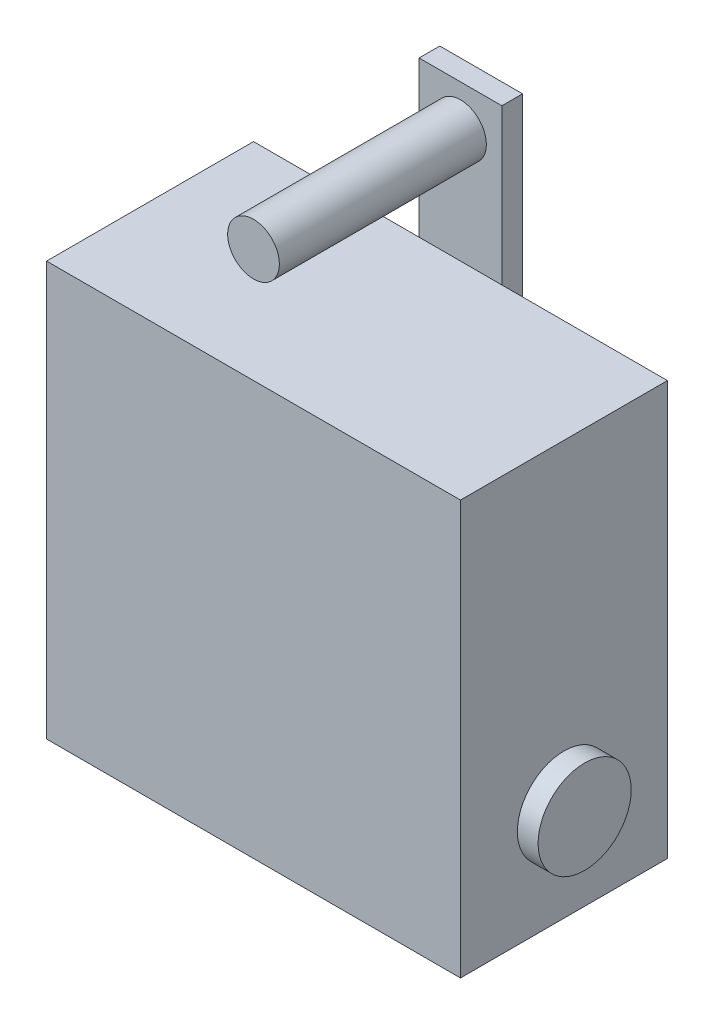
SolidWorks part; units mm, degrees
ref_plane "Plan de face" through (0, 0, 0) normal (0, 0, 1) x (1, 0, 0)
ref_plane "Plan de dessus" through (0, 0, 0) normal (0, 1, 0) x (1, 0, 0)
ref_plane "Plan de droite" through (0, 0, 0) normal (1, 0, 0) x (0, 0, -1)
sketch "Esquisse1" plane through (0, 0, 0) normal (0, 1, 0) x (1, 0, 0)
  line L1 (0, 0) -> (40, 0)
  line L2 (0, 0) -> (0, 20)
  line L3 (0, 20) -> (40, 20)
  line L4 (40, 0) -> (40, 20)
  dimension "D1" = 40
  dimension "D2" = 20
extrude "Boss.-Extru.1" add sketch "Esquisse1" along normal blind 40
sketch "Esquisse2" plane through (40, 0, 0) normal (1, 0, 0) x (0, 0, -1)
  line L2 (0, 0) -> (20, 0) construction
  line L3 (0, 40) -> (0, 0) construction
  circle A0 centre (10, 9.5) radius 4.5
  dimension "D1" = 9.5
  dimension "D2" = 9
  dimension "D3" = 10
extrude "Boss.-Extru.2" add sketch "Esquisse2" along normal blind 2
sketch "Esquisse3" plane through (0, 0, -20) normal (0, 0, -1) x (-1, 0, 0)
  line L0 (-24, 30) -> (-16, 30)
  line L1 (-24, 30) -> (-24, 55)
  line L2 (-16, 30) -> (-16, 55)
  line L3 (-24, 55) -> (-16, 55)
  line L4 (-40, 40) -> (0, 40) construction
  line L5 (-24, 36.7303) -> (-40, 36.7303) construction
  line L6 (-40, 40) -> (-40, 0) construction
  line L7 (-16, 36.7303) -> (0, 36.7303) construction
  line L8 (0, 40) -> (0, 0) construction
  dimension "D1" = 8
  dimension "D2" = 25
  dimension "D3" = 15
extrude "Boss.-Extru.3" add sketch "Esquisse3" along normal blind 2
sketch "Esquisse4" plane through (0, 0, -20) normal (0, 0, 1) x (1, 0, 0)
  line L0 (16, 55) -> (24, 55) construction
  line L1 (24, 55) -> (24, 40) construction
  circle A0 centre (20, 51) radius 2.5
  dimension "D1" = 5
  dimension "D2" = 4
  dimension "D3" = 4
extrude "Boss.-Extru.4" add sketch "Esquisse4" along normal blind 20
